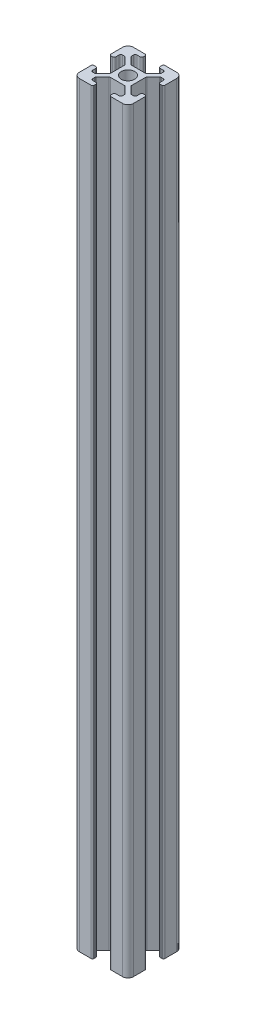
SolidWorks part; units mm, degrees
ref_plane "前视基准面" through (0, 0, 0) normal (0, 0, 1) x (1, 0, 0)
ref_plane "上视基准面" through (0, 0, 0) normal (0, 1, 0) x (1, 0, 0)
ref_plane "右视基准面" through (0, 0, 0) normal (1, 0, 0) x (0, 0, -1)
sketch "草图1" plane through (0, 0, 0) normal (0, 1, 0) x (1, 0, 0)
  line L0 (3.1, 8.8) -> (3.1, 9.4)
  line L1 (-10, -10) -> (10, -10) construction
  line L2 (-10, -10) -> (-10, 10) construction
  line L3 (-10, 10) -> (10, 10) construction
  line L4 (10, -10) -> (10, 10) construction
  line L5 (-10, -10) -> (10, 10) construction
  line L6 (-10, 10) -> (10, -10) construction
  line L7 (3.7, 10) -> (8, 10)
  line L8 (0, 10) -> (0, -10) construction
  line L9 (3.7, 8.2) -> (4.9, 8.2)
  line L10 (5.3243, 6.3849) -> (3.0151, 4.0757)
  line L11 (2.5908, 3.9) -> (0, 3.9)
  line L12 (5.5, 7.6) -> (5.5, 6.8092)
  line L13 (10, 3.7) -> (10, 8)
  line L14 (8.8, 3.1) -> (9.4, 3.1)
  line L15 (8.2, 3.7) -> (8.2, 4.9)
  line L16 (7.6, 5.5) -> (6.8092, 5.5)
  line L17 (6.3849, 5.3243) -> (4.0757, 3.0151)
  line L18 (3.9, 2.5908) -> (3.9, 0)
  line L19 (3.9, -2.5908) -> (3.9, 0)
  line L20 (2.5908, -3.9) -> (0, -3.9)
  line L21 (5.3243, -6.3849) -> (3.0151, -4.0757)
  line L22 (6.3849, -5.3243) -> (4.0757, -3.0151)
  line L23 (5.5, -7.6) -> (5.5, -6.8092)
  line L24 (3.7, -8.2) -> (4.9, -8.2)
  line L25 (3.1, -8.8) -> (3.1, -9.4)
  line L26 (3.7, -10) -> (8, -10)
  line L27 (10, -3.7) -> (10, -8)
  line L28 (8.8, -3.1) -> (9.4, -3.1)
  line L29 (8.2, -3.7) -> (8.2, -4.9)
  line L30 (7.6, -5.5) -> (6.8092, -5.5)
  line L31 (-2.5908, -3.9) -> (0, -3.9)
  line L32 (-3.9, -2.5908) -> (-3.9, 0)
  line L33 (-6.3849, -5.3243) -> (-4.0757, -3.0151)
  line L34 (-5.3243, -6.3849) -> (-3.0151, -4.0757)
  line L35 (-7.6, -5.5) -> (-6.8092, -5.5)
  line L36 (-8.2, -3.7) -> (-8.2, -4.9)
  line L37 (-8.8, -3.1) -> (-9.4, -3.1)
  line L38 (-10, -3.7) -> (-10, -8)
  line L39 (-3.7, -10) -> (-8, -10)
  line L40 (-3.1, -8.8) -> (-3.1, -9.4)
  line L41 (-3.7, -8.2) -> (-4.9, -8.2)
  line L42 (-5.5, -7.6) -> (-5.5, -6.8092)
  line L43 (-3.9, 2.5908) -> (-3.9, 0)
  line L44 (-2.5908, 3.9) -> (0, 3.9)
  line L45 (-5.3243, 6.3849) -> (-3.0151, 4.0757)
  line L46 (-6.3849, 5.3243) -> (-4.0757, 3.0151)
  line L47 (-5.5, 7.6) -> (-5.5, 6.8092)
  line L48 (-3.7, 8.2) -> (-4.9, 8.2)
  line L49 (-3.1, 8.8) -> (-3.1, 9.4)
  line L50 (-3.7, 10) -> (-8, 10)
  line L51 (-10, 3.7) -> (-10, 8)
  line L52 (-8.8, 3.1) -> (-9.4, 3.1)
  line L53 (-8.2, 3.7) -> (-8.2, 4.9)
  line L54 (-7.6, 5.5) -> (-6.8092, 5.5)
  circle A0 centre (0, 0) radius 2.5
  arc A1 (3.0151, 4.0757) -> (2.5908, 3.9) centre (2.5908, 4.5) cw
  arc A2 (5.5, 6.8092) -> (5.3243, 6.3849) centre (4.9, 6.8092) cw
  arc A3 (5.5, 7.6) -> (4.9, 8.2) centre (4.9, 7.6) ccw
  arc A4 (3.1, 8.8) -> (3.7, 8.2) centre (3.7, 8.8) ccw
  arc A5 (3.7, 10) -> (3.1, 9.4) centre (3.7, 9.4) ccw
  arc A6 (10, 3.7) -> (9.4, 3.1) centre (9.4, 3.7) cw
  arc A7 (8.8, 3.1) -> (8.2, 3.7) centre (8.8, 3.7) cw
  arc A8 (7.6, 5.5) -> (8.2, 4.9) centre (7.6, 4.9) cw
  arc A9 (6.8092, 5.5) -> (6.3849, 5.3243) centre (6.8092, 4.9) ccw
  arc A10 (4.0757, 3.0151) -> (3.9, 2.5908) centre (4.5, 2.5908) ccw
  arc A11 (10, 8) -> (8, 10) centre (8, 8) ccw
  arc A12 (3.0151, -4.0757) -> (2.5908, -3.9) centre (2.5908, -4.5) ccw
  arc A13 (4.0757, -3.0151) -> (3.9, -2.5908) centre (4.5, -2.5908) cw
  arc A14 (5.5, -6.8092) -> (5.3243, -6.3849) centre (4.9, -6.8092) ccw
  arc A15 (6.8092, -5.5) -> (6.3849, -5.3243) centre (6.8092, -4.9) cw
  arc A16 (5.5, -7.6) -> (4.9, -8.2) centre (4.9, -7.6) cw
  arc A17 (3.1, -8.8) -> (3.7, -8.2) centre (3.7, -8.8) cw
  arc A18 (3.7, -10) -> (3.1, -9.4) centre (3.7, -9.4) cw
  arc A19 (8, -10) -> (10, -8) centre (8, -8) ccw
  arc A20 (10, -3.7) -> (9.4, -3.1) centre (9.4, -3.7) ccw
  arc A21 (8.8, -3.1) -> (8.2, -3.7) centre (8.8, -3.7) ccw
  arc A22 (7.6, -5.5) -> (8.2, -4.9) centre (7.6, -4.9) ccw
  arc A23 (-4.0757, -3.0151) -> (-3.9, -2.5908) centre (-4.5, -2.5908) ccw
  arc A24 (-3.0151, -4.0757) -> (-2.5908, -3.9) centre (-2.5908, -4.5) cw
  arc A25 (-6.8092, -5.5) -> (-6.3849, -5.3243) centre (-6.8092, -4.9) ccw
  arc A26 (-5.5, -6.8092) -> (-5.3243, -6.3849) centre (-4.9, -6.8092) cw
  arc A27 (-7.6, -5.5) -> (-8.2, -4.9) centre (-7.6, -4.9) cw
  arc A28 (-8.8, -3.1) -> (-8.2, -3.7) centre (-8.8, -3.7) cw
  arc A29 (-10, -3.7) -> (-9.4, -3.1) centre (-9.4, -3.7) cw
  arc A30 (-10, -8) -> (-8, -10) centre (-8, -8) ccw
  arc A31 (-3.7, -10) -> (-3.1, -9.4) centre (-3.7, -9.4) ccw
  arc A32 (-3.1, -8.8) -> (-3.7, -8.2) centre (-3.7, -8.8) ccw
  arc A33 (-5.5, -7.6) -> (-4.9, -8.2) centre (-4.9, -7.6) ccw
  arc A34 (-3.0151, 4.0757) -> (-2.5908, 3.9) centre (-2.5908, 4.5) ccw
  arc A35 (-4.0757, 3.0151) -> (-3.9, 2.5908) centre (-4.5, 2.5908) cw
  arc A36 (-5.5, 6.8092) -> (-5.3243, 6.3849) centre (-4.9, 6.8092) ccw
  arc A37 (-6.8092, 5.5) -> (-6.3849, 5.3243) centre (-6.8092, 4.9) cw
  arc A38 (-5.5, 7.6) -> (-4.9, 8.2) centre (-4.9, 7.6) cw
  arc A39 (-3.1, 8.8) -> (-3.7, 8.2) centre (-3.7, 8.8) cw
  arc A40 (-3.7, 10) -> (-3.1, 9.4) centre (-3.7, 9.4) cw
  arc A41 (-8, 10) -> (-10, 8) centre (-8, 8) ccw
  arc A42 (-10, 3.7) -> (-9.4, 3.1) centre (-9.4, 3.7) ccw
  arc A43 (-8.8, 3.1) -> (-8.2, 3.7) centre (-8.8, 3.7) ccw
  arc A44 (-7.6, 5.5) -> (-8.2, 4.9) centre (-7.6, 4.9) ccw
  point P0 (0, 0)
  point P20 (5.5, 6.5607)
  point P25 (3.1, 8.2)
  point P28 (3.1, 10)
  point P156 (0, 0)
  dimension "D3" = 5
  dimension "D9" = 0.6
  dimension "D10" = 2
  dimension "D1" = 20
  dimension "D2" = 20
  dimension "D4" = 6.1
  dimension "D5" = 1.5
  dimension "D6" = 1.8
  dimension "D7" = 3.1
  dimension "D8" = 4.5
  dimension "D11" = 4
extrude "凸台-拉伸1" add sketch "草图1" along normal blind 280
